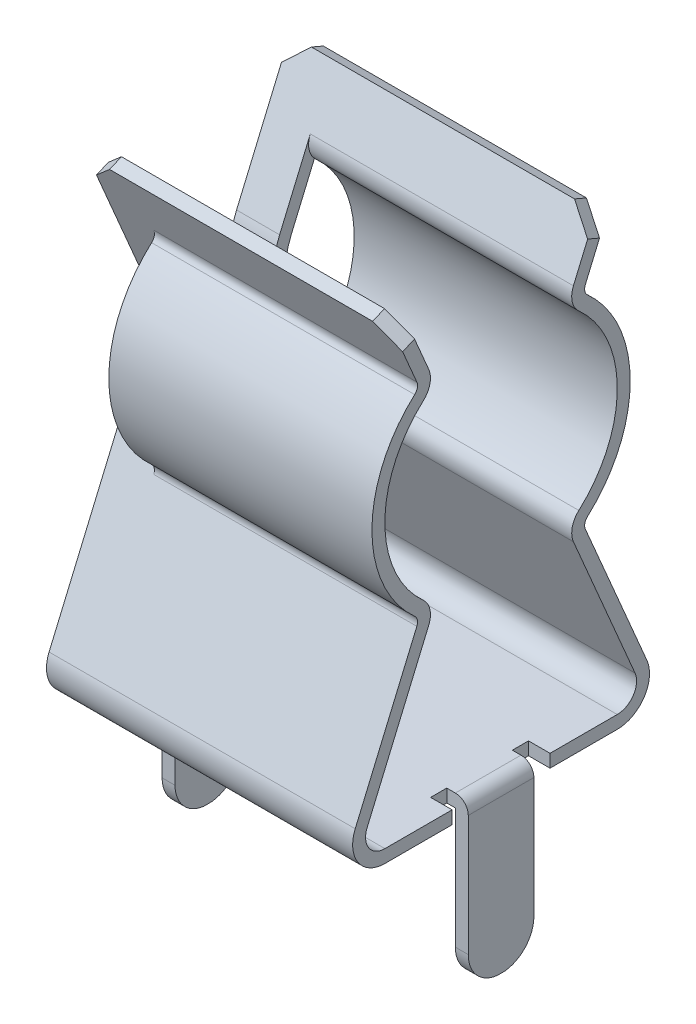
SolidWorks part; units mm, degrees
ref_plane "Front Plane" through (0, 0, 0) normal (0, 0, 1) x (1, 0, 0)
ref_plane "Top Plane" through (0, 0, 0) normal (0, 1, 0) x (1, 0, 0)
ref_plane "Right Plane" through (0, 0, 0) normal (1, 0, 0) x (0, 0, -1)
sketch "Sketch1" plane through (0, 0, 0) normal (1, 0, 0) x (0, 0, -1)
  line L0 (0, 0) -> (-52.175, 0) construction
  line L1 (0, 0) -> (0, 77.674) construction
  line L2 (0, 0) -> (-2.6983, 0)
  line L3 (0, 6.858) -> (-6.0398, 6.858) construction
  line L4 (-0.9676, 5.9558) -> (-3.1123, 0.9265)
  line L5 (-1.2434, 7.642) -> (-2.4827, 10.5504)
  line L6 (0, 0.3) -> (0, 0) construction
  line L7 (-0.9674, 7.7596) -> (-2.2067, 10.668)
  line L8 (-1.2436, 6.0735) -> (-3.3882, 1.0442)
  line L9 (2.2067, 10.668) -> (2.4827, 10.5504)
  line L10 (0, 0.3) -> (2.6983, 0.3)
  line L11 (1.2436, 6.0735) -> (3.3882, 1.0442)
  line L12 (0, 0.3) -> (-2.6983, 0.3)
  line L13 (0, 10.668) -> (-52.175, 10.668) construction
  line L14 (0.9674, 7.7596) -> (2.2067, 10.668)
  line L15 (1.2434, 7.642) -> (2.4827, 10.5504)
  line L16 (-2.2067, 10.668) -> (-2.4827, 10.5504)
  line L17 (0.9676, 5.9558) -> (3.1123, 0.9265)
  line L18 (-0.9674, 7.7596) -> (-3.0971, 12.7574) construction
  line L19 (-1.2434, 7.642) -> (-3.3731, 12.6398) construction
  line L20 (-0.9676, 5.9558) -> (-3.1123, 0.9265) construction
  line L21 (0, 0) -> (2.6983, 0)
  circle A0 centre (0, 6.858) radius 3.175 construction
  arc A1 (-1.2434, 7.642) -> (-1.2436, 6.0735) centre (-3.0833, 6.858) cw
  arc A2 (-2.6983, 0) -> (-3.3882, 1.0442) centre (-2.6983, 0.75) cw
  arc A3 (-0.9674, 7.7596) -> (-0.9676, 5.9558) centre (-3.0833, 6.858) cw
  arc A4 (2.6983, 0.3) -> (3.1123, 0.9265) centre (2.6983, 0.75) ccw
  arc A5 (0.9674, 7.7596) -> (0.9676, 5.9558) centre (3.0833, 6.858) ccw
  arc A6 (2.6983, 0) -> (3.3882, 1.0442) centre (2.6983, 0.75) ccw
  arc A7 (-2.6983, 0.3) -> (-3.1123, 0.9265) centre (-2.6983, 0.75) cw
  arc A8 (1.2434, 7.642) -> (1.2436, 6.0735) centre (3.0833, 6.858) ccw
  point P0 (0.35, 6.858)
  point P15 (-3.937, 10.668)
  point P17 (-1.3258, 7.8945)
  point P19 (-0.35, 6.858)
  point P21 (-3.7186, 10.8736)
  point P22 (-1.1074, 8.1001)
  dimension "D3" = 0.3
  dimension "D1" = 0.75
  dimension "D2" = 2
  dimension "D4" = 10.668
extrude "Boss-Extrude1" add sketch "Sketch1" along normal blind 1
sketch "Sketch2" plane through (1, 0, 0) normal (1, 0, 0) x (0, 0, -1)
  line L0 (0, 0) -> (0, 10.668) construction
  line L1 (0, 0) -> (-7.7536, 0) construction
  line L2 (0, 6.858) -> (-7.7536, 6.858) construction
  line L4 (-1.9567, 4.401) -> (-3.3882, 1.0442)
  line L6 (1.9564, 9.3152) -> (2.4827, 10.5504)
  line L12 (-2.6983, 0) -> (2.6983, 0)
  line L13 (3.3882, 1.0442) -> (1.2436, 6.0735)
  line L14 (1.2434, 7.642) -> (2.4827, 10.5504)
  line L15 (2.4827, 10.5504) -> (2.2067, 10.668)
  line L16 (2.2067, 10.668) -> (0.9674, 7.7596)
  line L17 (0.9676, 5.9558) -> (3.1123, 0.9265)
  line L18 (2.6983, 0.3) -> (-2.6983, 0.3)
  line L19 (-3.1123, 0.9265) -> (-0.9676, 5.9558)
  line L20 (-0.9674, 7.7596) -> (-2.2067, 10.668)
  line L21 (-2.2067, 10.668) -> (-2.4827, 10.5504)
  line L22 (-2.4827, 10.5504) -> (-1.2434, 7.642)
  line L23 (-1.2436, 6.0735) -> (-3.3882, 1.0442)
  line L24 (-2.6983, 0) -> (2.6983, 0)
  line L25 (3.3882, 1.0442) -> (1.9567, 4.401)
  line L27 (2.4827, 10.5504) -> (2.2067, 10.668)
  line L28 (2.2067, 10.668) -> (1.6804, 9.4329)
  line L29 (1.6808, 4.2834) -> (3.1123, 0.9265)
  line L30 (2.6983, 0.3) -> (-2.6983, 0.3)
  line L31 (-3.1123, 0.9265) -> (-1.6808, 4.2834)
  line L32 (-1.6804, 9.4329) -> (-2.2067, 10.668)
  line L33 (-2.2067, 10.668) -> (-2.4827, 10.5504)
  line L34 (-2.4827, 10.5504) -> (-1.9564, 9.3152)
  arc A0 (-1.8059, 8.8652) -> (-1.8062, 4.8511) centre (0, 6.858) ccw
  circle A1 centre (0, 6.858) radius 3 construction
  circle A2 centre (0, 6.858) radius 2.7 construction
  arc A3 (-2.0066, 9.0882) -> (-2.0069, 4.6281) centre (0, 6.858) ccw
  arc A4 (-1.9564, 9.3152) -> (-2.0066, 9.0882) centre (-2.1403, 9.2368) cw
  arc A5 (-2.0069, 4.6281) -> (-1.9567, 4.401) centre (-2.1407, 4.4795) cw
  arc A6 (2.0069, 4.6281) -> (1.9567, 4.401) centre (2.1407, 4.4795) ccw
  arc A7 (1.9564, 9.3152) -> (2.0066, 9.0882) centre (2.1403, 9.2368) ccw
  arc A8 (-3.3882, 1.0442) -> (-2.6983, 0) centre (-2.6983, 0.75) ccw
  arc A9 (2.6983, 0) -> (3.3882, 1.0442) centre (2.6983, 0.75) ccw
  arc A10 (1.2434, 7.642) -> (1.2436, 6.0735) centre (3.0833, 6.858) ccw
  arc A11 (0.9674, 7.7596) -> (0.9676, 5.9558) centre (3.0833, 6.858) ccw
  arc A12 (2.6983, 0.3) -> (3.1123, 0.9265) centre (2.6983, 0.75) ccw
  arc A13 (-3.1123, 0.9265) -> (-2.6983, 0.3) centre (-2.6983, 0.75) ccw
  arc A14 (-0.9676, 5.9558) -> (-0.9674, 7.7596) centre (-3.0833, 6.858) ccw
  arc A15 (-1.2436, 6.0735) -> (-1.2434, 7.642) centre (-3.0833, 6.858) ccw
  arc A16 (-3.3882, 1.0442) -> (-2.6983, 0) centre (-2.6983, 0.75) ccw
  arc A17 (2.6983, 0) -> (3.3882, 1.0442) centre (2.6983, 0.75) ccw
  arc A18 (-1.6804, 9.4329) -> (-1.8059, 8.8652) centre (-2.1403, 9.2368) cw
  arc A19 (-1.6808, 4.2834) -> (-1.8062, 4.8511) centre (-2.1407, 4.4795) ccw
  arc A20 (2.6983, 0.3) -> (3.1123, 0.9265) centre (2.6983, 0.75) ccw
  arc A21 (-3.1123, 0.9265) -> (-2.6983, 0.3) centre (-2.6983, 0.75) ccw
  arc A22 (1.6808, 4.2834) -> (1.8062, 4.8511) centre (2.1407, 4.4795) cw
  arc A23 (1.8059, 8.8652) -> (1.6804, 9.4329) centre (2.1403, 9.2368) cw
  arc A26 (2.0069, 4.6281) -> (2.0066, 9.0882) centre (0, 6.858) ccw
  arc A27 (1.8062, 4.8511) -> (1.8059, 8.8652) centre (0, 6.858) ccw
  point P34 (3.475, 6.858)
  point P35 (0.0002, 6.8582)
  point P36 (2.7, 6.858)
  point P37 (3.0363, 7.7863)
  point P38 (2.8689, 7.7351)
  point P49 (2.092, 9.6331)
  dimension "D3" = 0.2
  dimension "D4" = 0.2
  dimension "D5" = 0.2
  dimension "D6" = 0.2
  dimension "D7" = 0.5
  dimension "D8" = 0.5
  dimension "D9" = 0.3
  dimension "D10" = 0.5
  dimension "D11" = 0.5
  dimension "D1" = 0
  dimension "D2" = 6.858
extrude "Boss-Extrude2" add sketch "Sketch2" along normal blind 6.112
chamfer "Chamfer1" distance 0.5 angle 45 4 edges at (0, 10.6092, -2.3447) (7.112, 10.6092, -2.3447) (7.112, 10.6092, 2.3447) (0, 10.6092, 2.3447)
sketch "Sketch3" plane through (0, 0, 0) normal (0, -1, 0) x (1, 0, 0)
  line L0 (0, 0) -> (8.5128, 0) construction
  line L1 (0, 0) -> (0, 3.8569) construction
  line L2 (0.5, -1.137) -> (0.5, -0.762)
  line L3 (0.5, 0) -> (0.5, 3.8569) construction
  line L4 (0, -0.762) -> (0.5, -0.762)
  line L5 (0, 0.762) -> (0.5, 0.762)
  line L6 (0, 1.137) -> (0.5, 1.137)
  line L7 (0, -1.137) -> (0.5, -1.137)
  line L8 (0.5, 0.762) -> (0.5, 1.137)
  line L9 (0, 1.137) -> (8.5128, 1.137) construction
  line L10 (0, 0.762) -> (8.5128, 0.762) construction
  line L11 (0, 1.137) -> (0, 0.762)
  line L12 (0, -0.762) -> (8.5128, -0.762) construction
  line L13 (0, -1.137) -> (8.5128, -1.137) construction
  line L14 (0, -0.762) -> (0, -1.137)
  line L15 (3.556, 3.4483) -> (3.556, -3.4483) construction
  line L16 (7.112, 3.4483) -> (0, 3.4483) construction
  line L17 (0, -3.4483) -> (7.112, -3.4483) construction
  line L18 (7.112, -0.762) -> (7.112, -1.137)
  line L19 (7.112, 1.137) -> (7.112, 0.762)
  line L20 (6.612, 0.762) -> (6.612, 1.137)
  line L21 (7.112, -1.137) -> (6.612, -1.137)
  line L22 (7.112, 1.137) -> (6.612, 1.137)
  line L23 (7.112, 0.762) -> (6.612, 0.762)
  line L24 (7.112, -0.762) -> (6.612, -0.762)
  line L25 (6.612, -1.137) -> (6.612, -0.762)
  dimension "D1" = 0.5
  dimension "D2" = 0.762
  dimension "D3" = 0.762
  dimension "D4" = 0.375
  dimension "D5" = 0.375
extrude "Cut-Extrude1" cut sketch "Sketch3" against normal up to surface (0.3 mm away) up to face at (3.556, 0.3, 0)
sketch "Sketch4" plane through (0, 0, 0) normal (0, -1, 0) x (1, 0, 0)
  line L1 (0.3, 0.762) -> (0, 0.762)
  line L2 (0.3, 0.762) -> (0.3, -0.762)
  line L3 (0.3, 0.762) -> (0.3, -0.762)
  line L4 (0, 0.762) -> (0, -0.762)
  line L5 (0, -0.762) -> (0.3, -0.762)
  line L6 (3.556, -3.4483) -> (3.556, 3.5787) construction
  line L7 (0, -3.4483) -> (7.112, -3.4483) construction
  line L8 (7.112, -0.762) -> (6.812, -0.762)
  line L9 (7.112, 0.762) -> (7.112, -0.762)
  line L10 (6.812, 0.762) -> (6.812, -0.762)
  line L11 (6.812, 0.762) -> (7.112, 0.762)
  dimension "D1" = 0.3
extrude "Boss-Extrude3" add sketch "Sketch4" along normal blind 3.556
sketch "Sketch5" plane through (0, 0, 0) normal (-1, 0, 0) x (0, 0, 1)
  line L0 (-0.762, -2.8005) -> (-0.762, -3.556)
  line L1 (-0.762, -3.556) -> (0, -3.5625)
  line L2 (0, -3.5625) -> (0.762, -3.556)
  line L3 (0.762, -3.556) -> (0.762, -2.8005)
  arc A0 (-0.762, -2.8005) -> (0.762, -2.8005) centre (0, -2.8005) ccw
  line M1 (0.762, -3.556) -> (0.762, 0.3)
  line M3 (-0.762, 0.3) -> (-0.762, -3.556)
  line M4 (-0.762, -3.556) -> (0.762, -3.556)
extrude "Cut-Extrude2" cut sketch "Sketch5" against normal through all contours A0 M3 M4 | A0 M4 M1
fillet "Fillet1" radius 0.3 2 edges at (7.112, 0.3, 0) (0, 0.3, 0)
